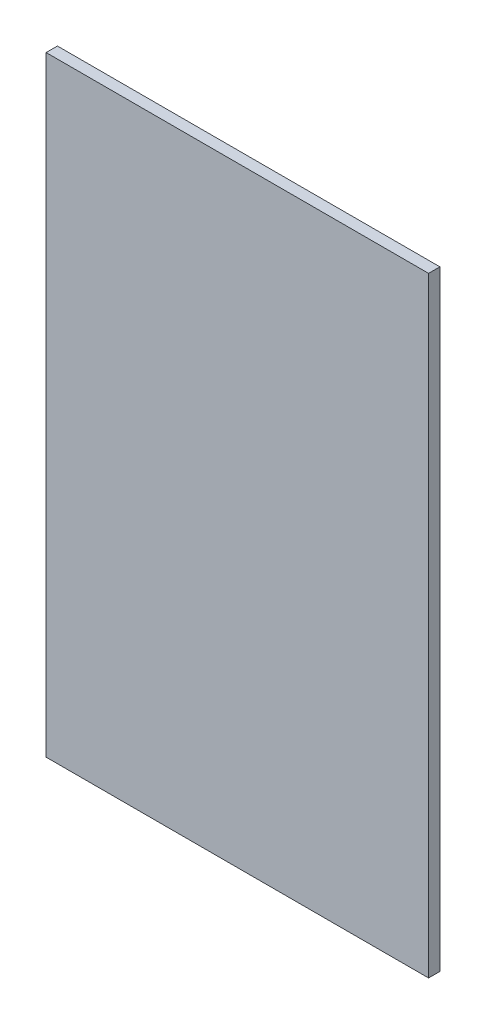
SolidWorks part; units mm, degrees
ref_plane "Front Plane" through (0, 0, 0) normal (0, 0, 1) x (1, 0, 0)
ref_plane "Top Plane" through (0, 0, 0) normal (0, 1, 0) x (1, 0, 0)
ref_plane "Right Plane" through (0, 0, 0) normal (1, 0, 0) x (0, 0, -1)
sketch "Sketch1" plane through (0, 0, 0) normal (0, 0, 1) x (1, 0, 0)
  line L8 (34.898, -88.9383) -> (34.898, -35.0104)
  line L9 (34.898, -35.0104) -> (1.098, -35.0104)
  line L10 (1.098, -35.0104) -> (1.098, -88.9383)
  line L11 (1.098, -88.9383) -> (34.898, -88.9383)
  line L12 (34.898, -88.9383) -> (34.898, -35.0104)
  line L13 (34.898, -35.0104) -> (1.098, -35.0104)
  line L14 (1.098, -35.0104) -> (1.098, -88.9383)
  line L15 (1.098, -88.9383) -> (34.898, -88.9383)
  dimension "D1" = 0.1
extrude "Boss-Extrude1" add sketch "Sketch1" along normal blind 1
